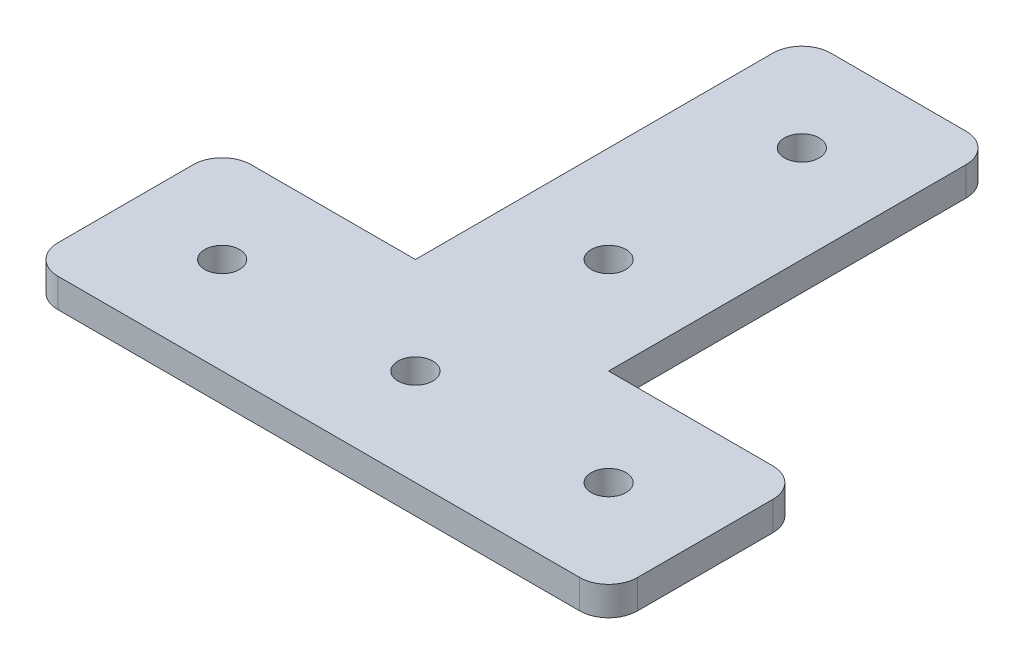
SolidWorks part; units mm, degrees
ref_plane "前视基准面" through (0, 0, 0) normal (0, 0, 1) x (1, 0, 0)
ref_plane "上视基准面" through (0, 0, 0) normal (0, 1, 0) x (1, 0, 0)
ref_plane "右视基准面" through (0, 0, 0) normal (1, 0, 0) x (0, 0, -1)
sketch "草图2" plane through (0, 0, 0) normal (0, 1, 0) x (1, 0, 0)
  line L0 (0, 0) -> (0, 18.4967) construction
  line L1 (-30, -10) -> (30, -10)
  line L2 (-30, -10) -> (-30, 10)
  line L3 (-30, 10) -> (30, 10)
  line L4 (30, -10) -> (30, 10)
  line L5 (-30, -10) -> (30, 10) construction
  line L6 (-30, 10) -> (30, -10) construction
  line L7 (-10, 50) -> (10, 50)
  line L8 (-10, 50) -> (-10, 10)
  line L9 (-10, 10) -> (10, 10)
  line L10 (10, 50) -> (10, 10)
  circle A0 centre (0, 40) radius 1.8
  circle A1 centre (0, 20) radius 1.8
  circle A2 centre (20, 0) radius 1.8
  circle A3 centre (-20, 0) radius 1.8
  circle A4 centre (0, 0) radius 1.8
  point P0 (0, 0)
  dimension "D5" = 3.6
  dimension "D1" = 20
  dimension "D2" = 60
  dimension "D3" = 20
  dimension "D4" = 40
  dimension "D6" = 20
  dimension "D7" = 20
  dimension "D8" = 20
  dimension "D9" = 20
extrude "凸台-拉伸1" add sketch "草图2" along normal blind 3 contours L10 L7 L8 L3 A1 A0 | L1 L4 L3 L2 A4 A3 A2
fillet "圆角1" radius 3 6 edges at (10, 1.5, -50) (30, 1.5, -10) (30, 1.5, 10) (-30, 1.5, 10) (-30, 1.5, -10) (-10, 1.5, -50)
